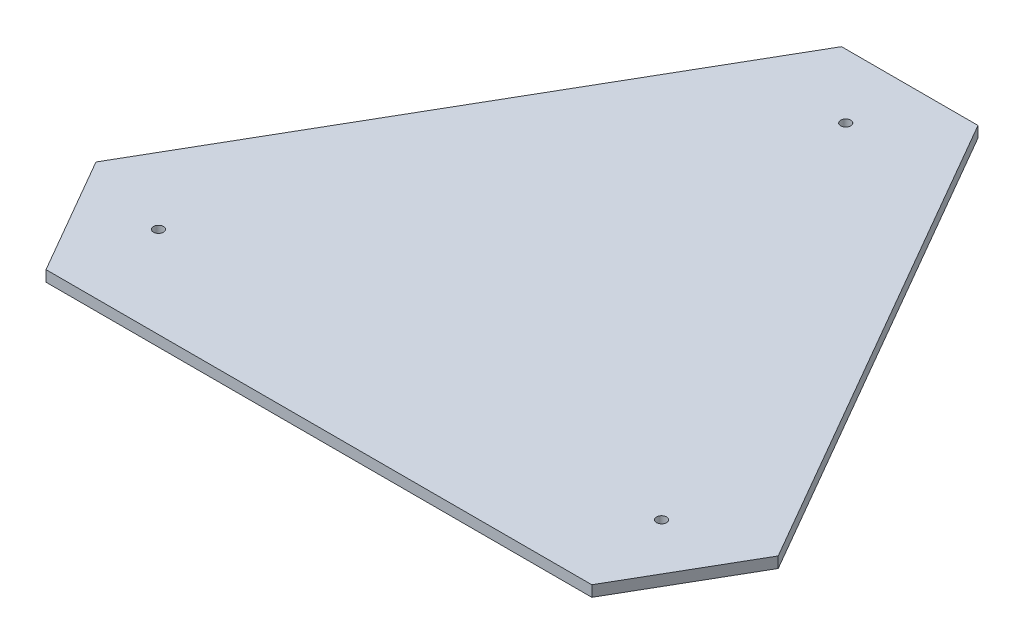
SolidWorks part; units mm, degrees
ref_plane "Plan de face" through (0, 0, 0) normal (0, 0, 1) x (1, 0, 0)
ref_plane "Plan de dessus" through (0, 0, 0) normal (0, 1, 0) x (1, 0, 0)
ref_plane "Plan de droite" through (0, 0, 0) normal (1, 0, 0) x (0, 0, -1)
sketch "Esquisse1" plane through (0, 0, 0) normal (0, 1, 0) x (1, 0, 0)
  line L0 (-37.5, 194.8557) -> (37.5, 194.8557)
  line L1 (37.5, 194.8557) -> (187.5, -64.9519)
  line L2 (187.5, -64.9519) -> (150, -129.9038)
  line L3 (150, -129.9038) -> (-150, -129.9038)
  line L4 (-150, -129.9038) -> (-187.5, -64.9519)
  line L5 (-187.5, -64.9519) -> (-37.5, 194.8557)
  line L6 (0, 194.8557) -> (0, 0) construction
  line L7 (0, 0) -> (168.75, -97.4279) construction
  line L8 (-168.75, -97.4279) -> (0, 0) construction
  line L9 (-112.5, 64.9519) -> (0, 0) construction
  line L10 (0, 0) -> (0, -129.9038) construction
  line L11 (112.5, 64.9519) -> (0, 0) construction
  line L12 (-37.5, 194.8557) -> (0, 259.8076) construction
  line L13 (0, 259.8076) -> (37.5, 194.8557) construction
  line L14 (-187.5, -64.9519) -> (-225, -129.9038) construction
  line L15 (-225, -129.9038) -> (-150, -129.9038) construction
  point P14 (-188.5206, -107.3077)
  point P16 (0, 106.812)
  point P18 (-33.2902, 155.9593)
  dimension "D1" = 450
  dimension "D2" = 120
  dimension "D3" = 300
extrude "Boss.-Extru.1" add sketch "Esquisse1" along normal blind 6
ref_plane "Plan1" through (-18.75, 0, 32.476) normal (-0.5, 0, 0.866) x (0, -1, 0)
ref_plane "Plan2" through (18.75, 0, -32.476) normal (-0.5, 0, 0.866) x (0, -1, 0)
ref_plane "Plan3" through (0, 0, 0) normal (-0.5, 0, 0.866) x (0.866, 0, 0.5)
sketch "Esquisse2" plane through (0, 6, 0) normal (0, 1, 0) x (1, 0, 0)
  circle A0 centre (0, 159.6414) radius 2.75
  circle A1 centre (-138.2535, -79.8207) radius 2.75
  circle A2 centre (138.2535, -79.8207) radius 2.75
  point P9 (0, 0)
  point P11 (0, 0)
  dimension "D1" = 5.5
  dimension "D2" = 138.2535
  dimension "D3" = 138.2535
  dimension "D4" = 159.6414
  dimension "D5" = 79.8207
extrude "Enlèv. mat.-Extru.1" cut sketch "Esquisse2" against normal up to next
equation "\"epaisseu\"=6"
equation "\"D1@Boss.-Extru.1\"=\"epaisseu\""
